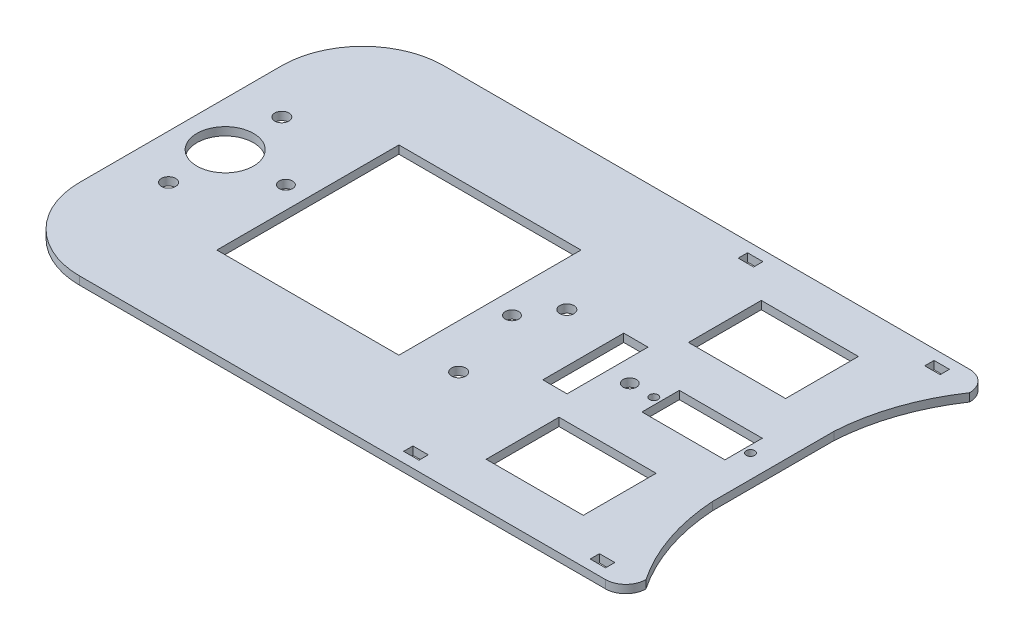
SolidWorks part; units mm, degrees
ref_plane "Front" through (0, 0, 0) normal (0, 0, 1) x (1, 0, 0)
ref_plane "Top" through (0, 0, 0) normal (0, 1, 0) x (1, 0, 0)
ref_plane "Right" through (0, 0, 0) normal (1, 0, 0) x (0, 0, -1)
sketch "Croquis1" plane through (0, 0, 0) normal (0, 1, 0) x (1, 0, 0)
  line L0 (-677.3338, 0) -> (33189.3559, 0) construction
  line L1 (0, -677.3338) -> (0, 33189.3559) construction
  line L2 (-58.4622, -14) -> (-58.4622, 14) construction
  line L3 (-49.4622, -45) -> (80.5378, -45)
  line L4 (-69.4622, -25) -> (-69.4622, 25)
  line L5 (-49.4622, 45) -> (80.5378, 45)
  line L6 (-677.3338, -25) -> (33189.3559, -25) construction
  line L7 (-677.3338, 25) -> (33189.3559, 25) construction
  line L8 (40.0378, -16) -> (40.0378, -34)
  line L9 (49.1653, -4.625) -> (69.6653, -4.625)
  line L10 (49.1653, -4.625) -> (49.1653, 4.625)
  line L11 (30.0378, -962) -> (30.0378, 49038) construction
  line L12 (28.1378, 40.2) -> (31.9378, 40.2)
  line L13 (28.1378, 40.2) -> (28.1378, 42.5)
  line L14 (28.1378, 42.5) -> (31.9378, 42.5)
  line L15 (31.9378, 40.2) -> (31.9378, 42.5)
  line L16 (28.1378, 40.2) -> (31.9378, 42.5) construction
  line L17 (28.1378, 42.5) -> (31.9378, 40.2) construction
  line L18 (76.1378, -960.85) -> (76.1378, 49039.15) construction
  line L19 (78.0378, 40.2) -> (78.0378, 42.5)
  line L20 (78.0378, 40.2) -> (74.2378, 40.2)
  line L21 (74.2378, 40.2) -> (74.2378, 42.5)
  line L22 (78.0378, 42.5) -> (74.2378, 42.5)
  line L23 (74.2378, -40.2) -> (74.2378, -42.5)
  line L24 (78.0378, -40.2) -> (74.2378, -40.2)
  line L25 (78.0378, -40.2) -> (78.0378, -42.5)
  line L26 (78.0378, -42.5) -> (74.2378, -42.5)
  line L27 (28.1378, -40.2) -> (28.1378, -42.5)
  line L28 (28.1378, -40.2) -> (31.9378, -40.2)
  line L29 (31.9378, -40.2) -> (31.9378, -42.5)
  line L30 (28.1378, -42.5) -> (31.9378, -42.5)
  line L31 (-15.5222, -1000) -> (-15.5222, 49000) construction
  line L32 (37, -1000) -> (37, 49000) construction
  line L33 (49.1653, 4.625) -> (69.6653, 4.625)
  line L34 (77.0378, -15) -> (77.0378, 15)
  line L35 (30.0378, -10) -> (36.0378, -10)
  line L36 (30.0378, -10) -> (30.0378, 10)
  line L37 (30.0378, 10) -> (36.0378, 10)
  line L38 (36.0378, -10) -> (36.0378, 10)
  line L39 (30.0378, -10) -> (36.0378, 10) construction
  line L40 (30.0378, 10) -> (36.0378, -10) construction
  line L41 (69.6653, -4.625) -> (69.6653, 4.625)
  line L42 (49.1653, -4.625) -> (69.6653, 4.625) construction
  line L43 (49.1653, 4.625) -> (69.6653, -4.625) construction
  line L44 (-38.0222, -22.5) -> (6.9778, -22.5)
  line L45 (-38.0222, -22.5) -> (-38.0222, 22.5)
  line L46 (-38.0222, 22.5) -> (6.9778, 22.5)
  line L47 (6.9778, -22.5) -> (6.9778, 22.5)
  line L48 (-38.0222, -22.5) -> (6.9778, 22.5) construction
  line L49 (-38.0222, 22.5) -> (6.9778, -22.5) construction
  line L50 (40.0378, 16) -> (64.0378, 16)
  line L51 (40.0378, 16) -> (40.0378, 34)
  line L52 (40.0378, 34) -> (64.0378, 34)
  line L53 (64.0378, 16) -> (64.0378, 34)
  line L54 (40.0378, 16) -> (64.0378, 34) construction
  line L55 (40.0378, 34) -> (64.0378, 16) construction
  line L56 (40.0378, -16) -> (64.0378, -16)
  line L57 (64.0378, -16) -> (64.0378, -34)
  line L58 (40.0378, -34) -> (64.0378, -34)
  circle A0 centre (-58.4622, -14) radius 1.75
  circle A1 centre (-58.4622, 14) radius 1.75
  arc A2 (80.5378, -45) -> (85.5378, -40) centre (80.5378, -40) ccw
  circle A3 centre (71.3653, 0) radius 1.05
  circle A4 centre (47.4653, 0) radius 1.05
  arc A5 (85.5378, 40) -> (80.5378, 45) centre (80.5378, 40) ccw
  circle A6 centre (-43.4622, 0) radius 1.65
  circle A7 centre (12.4178, 0) radius 1.65
  arc A8 (-69.4622, 25) -> (-49.4622, 45) centre (-49.4622, 25) cw
  arc A9 (-49.4622, -45) -> (-69.4622, -25) centre (-49.4622, -25) cw
  circle A10 centre (-58.4622, 0) radius 7
  arc A11 (77.0378, 15) -> (85.5378, 40) centre (127.0772, 11.9316) cw
  arc A12 (77.0378, -15) -> (85.5378, -40) centre (127.0772, -11.9316) ccw
  circle A13 centre (41.5378, 0) radius 1.65
  circle A14 centre (17.9778, 8) radius 1.75
  circle A15 centre (17.9778, -18.7345) radius 1.75
  point P4 (0, 0)
  point P13 (-58.4622, 0)
  point P21 (30.0378, 41.35)
  point P42 (59.4153, 0)
  point P45 (77.0378, 0)
  point P47 (76.1378, 42.5)
  point P58 (-15.5222, 0)
  point P66 (33.0378, 0)
  point P75 (70, 15)
  point P86 (52.0378, 25)
  dimension "D5" = 3.5
  dimension "D6" = 90
  dimension "D12" = 30
  dimension "D14" = 26
  dimension "D15" = 3.3
  dimension "D17" = 14
  dimension "D18" = 20
  dimension "D19" = 20
  dimension "D23" = 5
  dimension "D13" = 3.3
  dimension "D16" = 55.88
  dimension "D24" = 27.94
  dimension "D27" = 14
  dimension "D33" = 2.1
  dimension "D34" = 5.6725
  dimension "D35" = 2.1
  dimension "D36" = 23.9
  dimension "D39" = 1.7
  dimension "D40" = 5.44
  dimension "D41" = 47
  dimension "D47" = 3.3
  dimension "D48" = 5.5
  dimension "D49" = 3.5
  dimension "D50" = 3.5
  dimension "D51" = 26.7345
  dimension "D52" = 17
  dimension "D53" = 11
  dimension "D3" = 28
  dimension "D4" = 11
  dimension "D8" = 3.8
  dimension "D9" = 41
  dimension "D11" = 46.1
  dimension "D20" = 20
  dimension "D21" = 6
  dimension "D22" = 2.3
  dimension "D10" = 146.5
  dimension "D25" = 45
  dimension "D26" = 45
  dimension "D7" = 130
  dimension "D28" = 2.5
  dimension "D29" = 3.8
  dimension "D30" = 2.3
  dimension "D31" = 2.5
  dimension "D32" = 2.5
  dimension "D37" = 20.5
  dimension "D38" = 9.25
  dimension "D44" = 24
  dimension "D45" = 18
  dimension "D46" = 13
  dimension "D42" = 25
  dimension "D43" = 25
extrude "Saliente-Extruir1" add sketch "Croquis1" along normal blind 2
sketch "Croquis2" [suppressed] plane through (0, 2, 0) normal (0, 1, 0) x (1, 0, 0)
  line L0 (-947.5, 0) -> (49052.5, 0) construction
  line L1 (62.5, -15) -> (62.5, 15) construction
  arc A0 (44.57, -4.8734) -> (44.57, 4.8734) centre (48.07, 0) ccw
  arc A1 (41.57, 3) -> (41.57, -3) centre (41.57, 0) ccw
  arc A2 (41.57, 3) -> (44.57, 4.8734) centre (41.023, 7.2147) ccw
  arc A3 (41.57, -3) -> (44.57, -4.8734) centre (41.023, -7.2147) cw
  point P5 (62.5, 0)
  dimension "D1" = 12
  dimension "D2" = 14.43
  dimension "D3" = 6
  dimension "D4" = 6.5
  dimension "D5" = 4.25
extrude "Cortar-Extruir1" [suppressed] cut sketch "Croquis2" against normal blind 10
